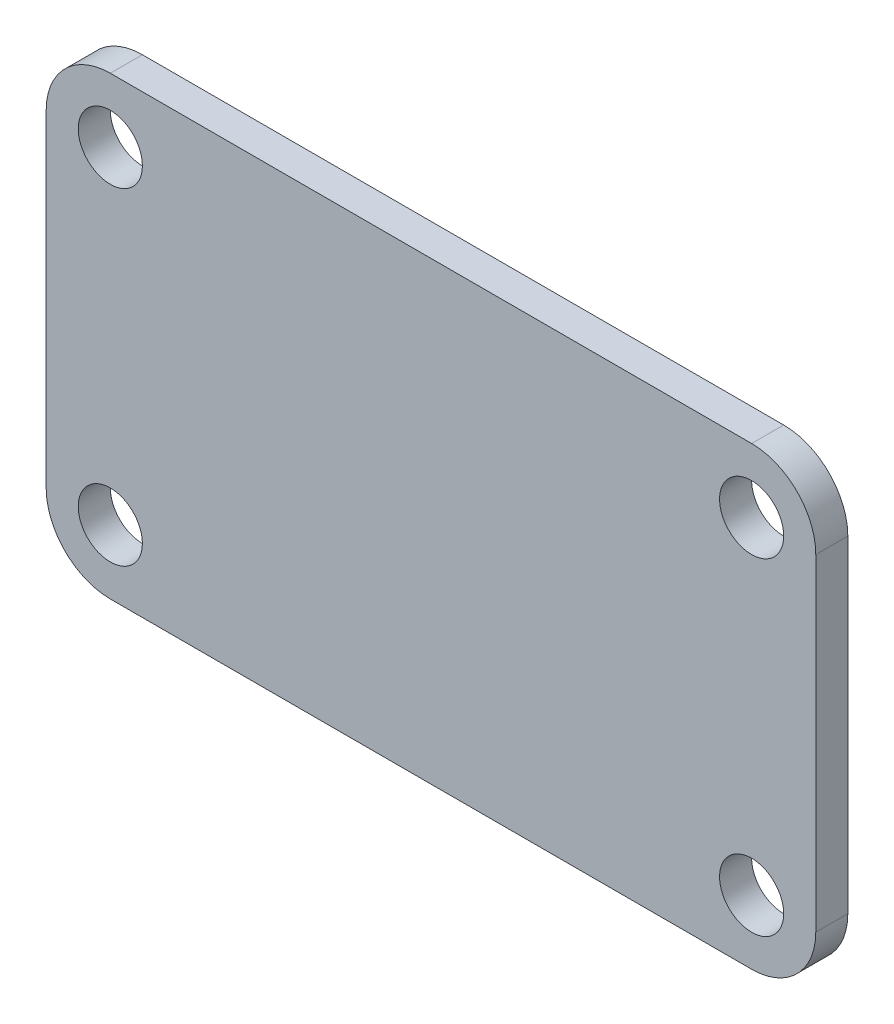
SolidWorks part; units mm, degrees
ref_plane "Front Plane" through (0, 0, 0) normal (0, 0, 1) x (1, 0, 0)
ref_plane "Top Plane" through (0, 0, 0) normal (0, 1, 0) x (1, 0, 0)
ref_plane "Right Plane" through (0, 0, 0) normal (1, 0, 0) x (0, 0, -1)
sketch "Sketch1" plane through (0, 0, 0) normal (0, 0, 1) x (1, 0, 0)
  line L0 (0, 12.954) -> (0, 0) construction
  line L1 (0, 0) -> (25.4, 0) construction
  line L2 (25.4, 0) -> (25.4, 12.954) construction
  line L3 (25.4, 12.954) -> (0, 12.954) construction
  line L4 (-2.54, 15.494) -> (-2.54, -2.54)
  line L5 (-2.54, -2.54) -> (27.94, -2.54)
  line L6 (27.94, -2.54) -> (27.94, 15.494)
  line L7 (27.94, 15.494) -> (-2.54, 15.494)
  circle A0 centre (0, 12.954) radius 1.27
  circle A1 centre (0, 0) radius 1.27
  circle A2 centre (25.4, 12.954) radius 1.27
  circle A3 centre (25.4, 0) radius 1.27
  point P0 (0, 0)
  point P1 (0, 12.954)
  point P3 (25.4, 12.954)
  point P4 (25.4, 0)
  point P17 (0, 0)
  dimension "D3" = 2.54
  dimension "D1" = 25.4
  dimension "D2" = 12.954
  dimension "D5" = 12.954
  dimension "D4" = 2.54
extrude "Boss-Extrude1" add sketch "Sketch1" along normal blind 1.27
fillet "Fillet1" radius 2.54 4 edges at (-2.54, -2.54, 0.635) (27.94, -2.54, 0.635) (27.94, 15.494, 0.635) (-2.54, 15.494, 0.635)
